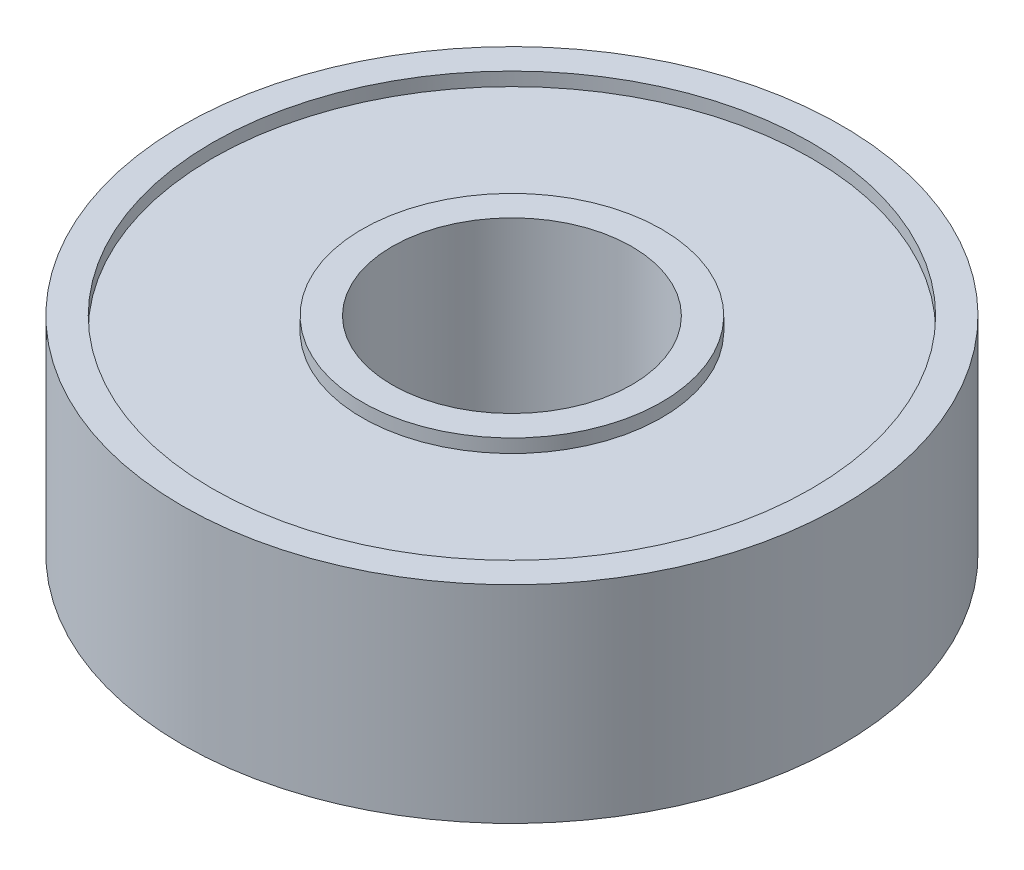
SolidWorks part; units mm, degrees
ref_plane "Front Plane" through (0, 0, 0) normal (0, 0, 1) x (1, 0, 0)
ref_plane "Top Plane" through (0, 0, 0) normal (0, 1, 0) x (1, 0, 0)
ref_plane "Right Plane" through (0, 0, 0) normal (1, 0, 0) x (0, 0, -1)
sketch "Sketch1" plane through (0, 0, 0) normal (0, 1, 0) x (1, 0, 0)
  circle A0 centre (0, 0) radius 11
  dimension "D1" = 22
extrude "Boss-Extrude1" add sketch "Sketch1" along normal mid plane 6
sketch "Sketch2" plane through (0, 0, 0) normal (0, 1, 0) x (1, 0, 0)
  circle A1 centre (0, 0) radius 11
  circle A2 centre (0, 0) radius 10
  dimension "D1" = 22
  dimension "D2" = 1
extrude "Boss-Extrude2" add sketch "Sketch2" along normal mid plane 6.9
sketch "Sketch4" plane through (0, 0, 0) normal (0, 1, 0) x (1, 0, 0)
  circle A0 centre (0, 0) radius 27.5915
  circle A2 centre (0, 0) radius 5
  dimension "D1" = 10
extrude "Boss-Extrude3" add sketch "Sketch4" along normal mid plane 6.9 contours A2
sketch "Sketch5" plane through (0, 3.45, 0) normal (0, 1, 0) x (1, 0, 0)
  circle A0 centre (0, 0) radius 4
  circle A2 centre (0, 0) radius 5 construction
  dimension "D1" = 1
extrude "Cut-Extrude1" cut sketch "Sketch5" against normal blind 10
